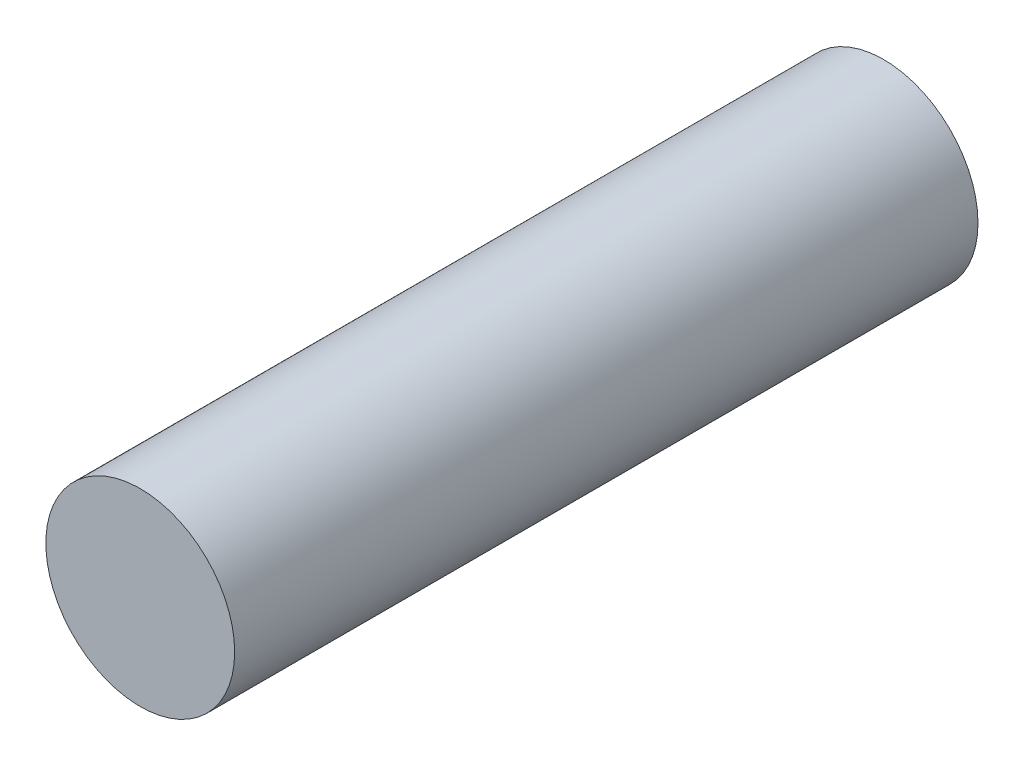
SolidWorks part; units mm, degrees
ref_plane "Alzado" through (0, 0, 0) normal (0, 0, 1) x (1, 0, 0)
ref_plane "Planta" through (0, 0, 0) normal (0, 1, 0) x (1, 0, 0)
ref_plane "Vista lateral" through (0, 0, 0) normal (1, 0, 0) x (0, 0, -1)
sketch "Croquis1" plane through (0, 0, 0) normal (0, 0, 1) x (1, 0, 0)
  circle A0 centre (0, 0) radius 6.35
  dimension "D1" = 12.7
extrude "Saliente-Extruir1" add sketch "Croquis1" along normal blind 50
